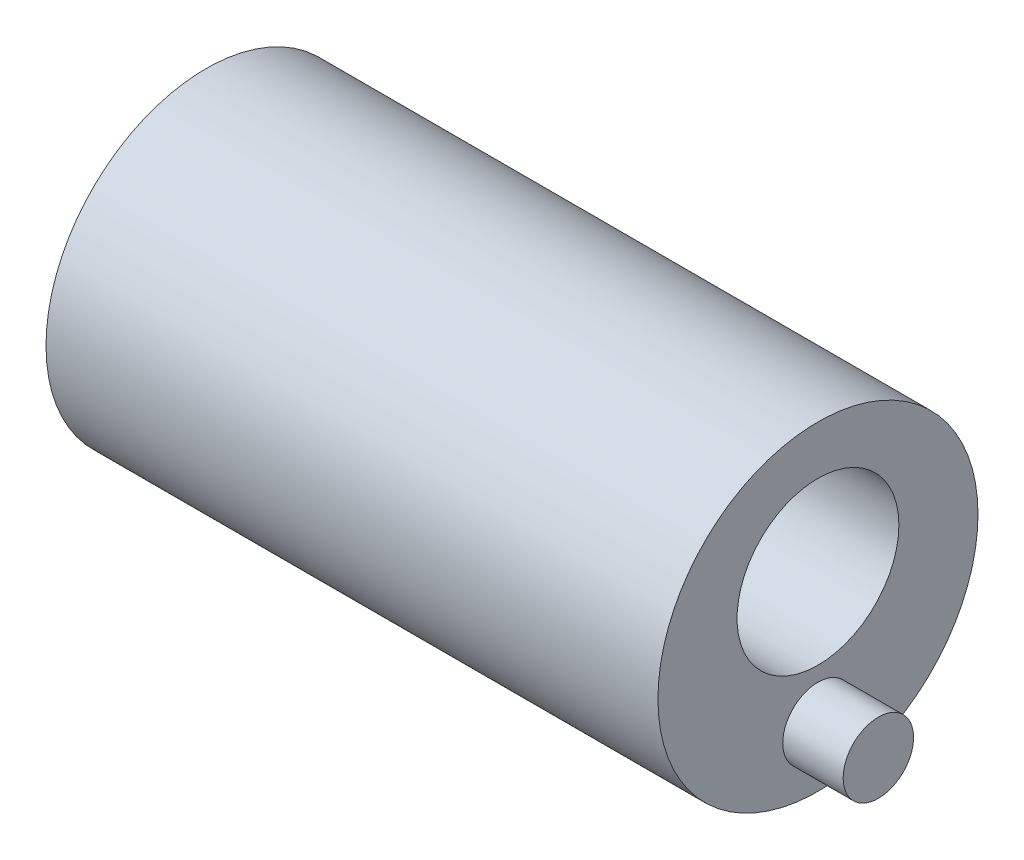
SolidWorks part; units mm, degrees
ref_plane "Front Plane" through (0, 0, 0) normal (0, 0, 1) x (1, 0, 0)
ref_plane "Top Plane" through (0, 0, 0) normal (0, 1, 0) x (1, 0, 0)
ref_plane "Right Plane" through (0, 0, 0) normal (1, 0, 0) x (0, 0, -1)
sketch "Sketch1" plane through (0, 0, 0) normal (1, 0, 0) x (0, 0, -1)
  circle A0 centre (0, 0) radius 100.965
  dimension "D1" = 201.93
extrude "Boss-Extrude1" add sketch "Sketch1" against normal blind 386.08
sketch "Sketch2" plane through (0, 0, 0) normal (1, 0, 0) x (0, 0, -1)
  line L0 (0, -998.1793) -> (0, 49001.8207) construction
  line L1 (-977.9245, 19.05) -> (49022.0755, 19.05) construction
  circle A0 centre (0, 19.05) radius 51.054
  dimension "D2" = 102.108
  dimension "D1" = 19.05
extrude "Cut-Extrude1" cut sketch "Sketch2" against normal through all
sketch "Sketch3" plane through (0, 0, 0) normal (1, 0, 0) x (0, 0, -1)
  line L0 (0, -1000) -> (0, 49000) construction
  line L1 (-1011.6067, -63.5) -> (48988.3933, -63.5) construction
  circle A0 centre (0, -63.5) radius 22.225
  dimension "D2" = 44.45
  dimension "D1" = 63.5
extrude "Boss-Extrude2" add sketch "Sketch3" along normal blind 38.1
